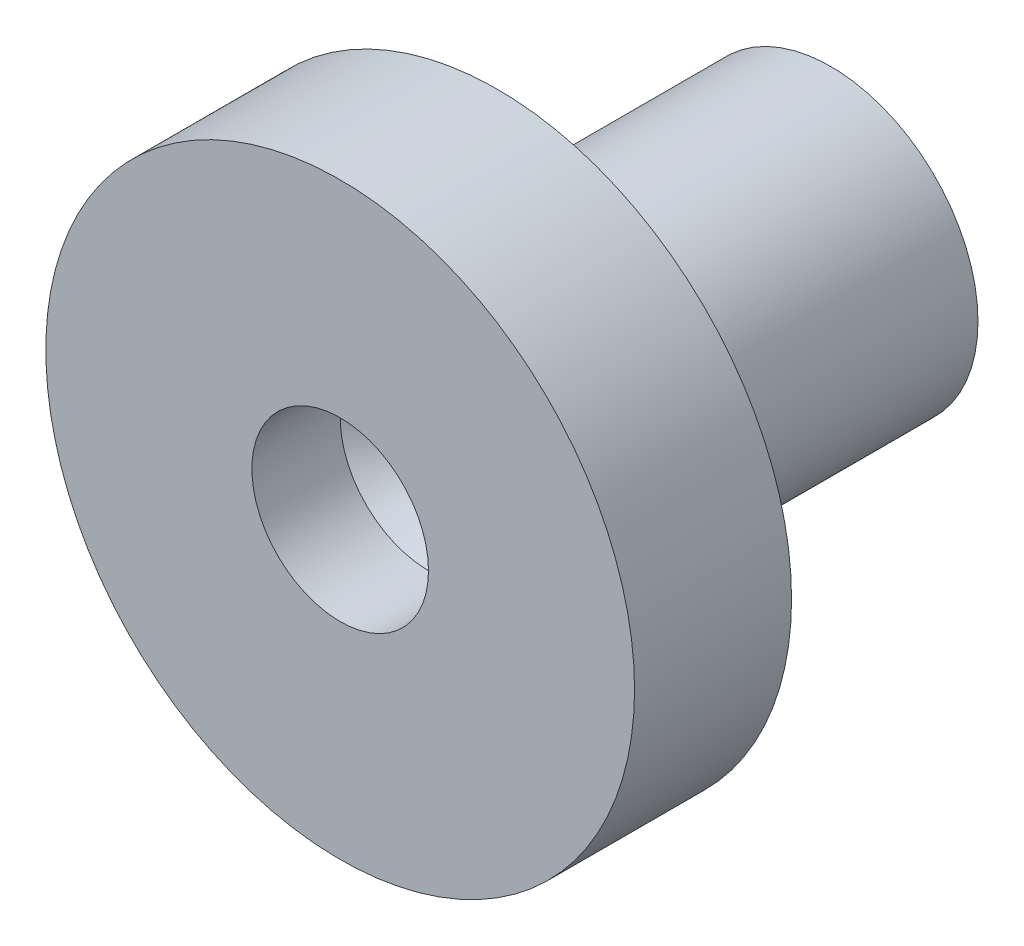
SolidWorks part; units mm, degrees
ref_plane "Спереди" through (0, 0, 0) normal (0, 0, 1) x (1, 0, 0)
ref_plane "Сверху" through (0, 0, 0) normal (0, 1, 0) x (1, 0, 0)
ref_plane "Справа" through (0, 0, 0) normal (1, 0, 0) x (0, 0, -1)
sketch "Эскиз1" plane through (0, 0, 0) normal (0, 0, 1) x (1, 0, 0)
  circle A0 centre (0, 0) radius 4.35
  circle A1 centre (0, 0) radius 7.5
  dimension "D1" = 8.7
  dimension "D2" = 15
extrude "Вытянуть1" add sketch "Эскиз1" along normal blind 17
sketch "Эскиз3" plane through (0, 0, 0) normal (0, 0, -1) x (-1, 0, 0)
  circle A0 centre (0, 0) radius 6
  dimension "D1" = 12
extrude "Вытянуть2" cut sketch "Эскиз3" against normal blind 3
sketch "Эскиз4" plane through (0, 0, 17) normal (0, 0, 1) x (1, 0, 0)
  circle A0 centre (0, 0) radius 7.5
  dimension "D1" = 15
extrude "Вытянуть3" add sketch "Эскиз4" along normal blind 8
sketch "Эскиз5" plane through (0, 0, 25) normal (0, 0, 1) x (1, 0, 0)
  circle A0 centre (0, 0) radius 1.25
  dimension "D1" = 2.5
extrude "Вытянуть4" cut sketch "Эскиз5" against normal mid plane 27
sketch "Эскиз6" plane through (0, 0, 25) normal (0, 0, 1) x (1, 0, 0)
  circle A0 centre (0, 0) radius 4.5
  dimension "D1" = 9
extrude "Вытянуть5" cut sketch "Эскиз6" against normal blind 4.5
sketch "Эскиз7" plane through (0, 0, 20.5) normal (0, 0, 1) x (1, 0, 0)
  circle A0 centre (0, 0) radius 4.5
  dimension "D1" = 9
extrude "Вытянуть6" cut sketch "Эскиз7" against normal blind 2.5 draft 50
sketch "Эскиз8" plane through (0, 0, 25) normal (0, 0, 1) x (1, 0, 0)
  circle A0 centre (0, 0) radius 15
  circle A1 centre (0, 0) radius 7.5
  dimension "D1" = 15
  dimension "D2" = 30
extrude "Вытянуть8" add sketch "Эскиз8" along normal blind 8 from offset 8
fillet "Скругление1" radius 3 1 edges at (7.5, 0, 17)
